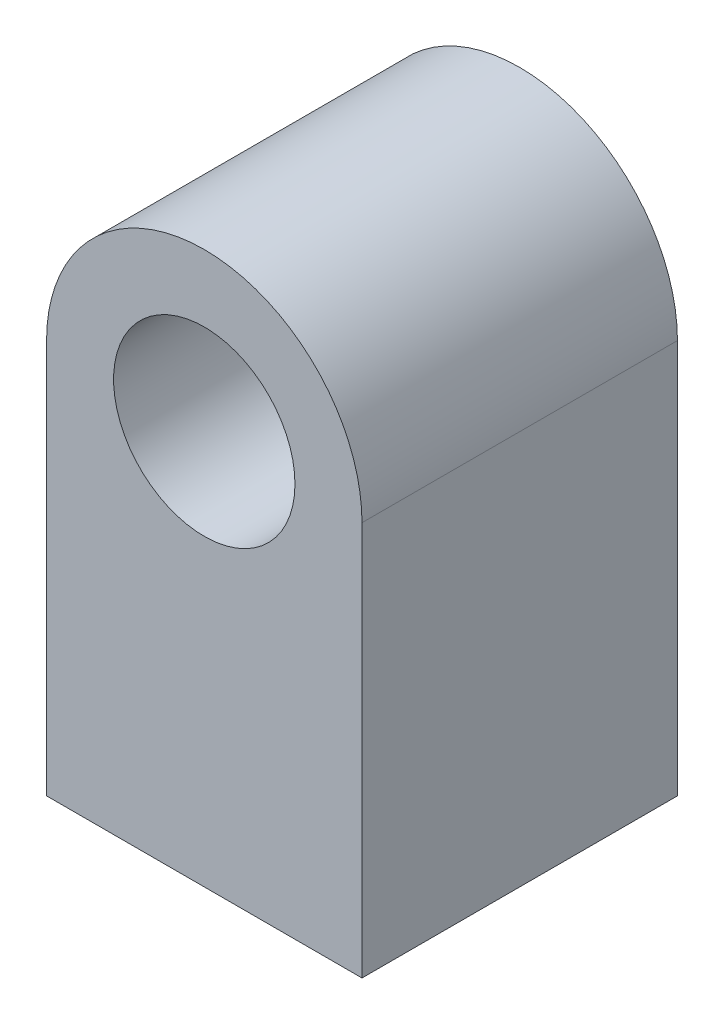
SolidWorks part; units mm, degrees
ref_plane "前视基准面" through (0, 0, 0) normal (0, 0, 1) x (1, 0, 0)
ref_plane "上视基准面" through (0, 0, 0) normal (0, 1, 0) x (1, 0, 0)
ref_plane "右视基准面" through (0, 0, 0) normal (1, 0, 0) x (0, 0, -1)
other "Configuration Table"
sketch "草图1" plane through (0, 0, 0) normal (0, 0, 1) x (1, 0, 0)
  line L0 (2, 0) -> (2, -5)
  line L1 (2, -5) -> (-2, -5)
  line L2 (-2, -5) -> (-2, 0)
  arc A0 (2, 0) -> (-2, 0) centre (0, 0) ccw
  circle A1 centre (0, 0) radius 1.15
  dimension "D1" = 2.3
  dimension "D2" = 2
  dimension "D3" = 5
extrude "凸台-拉伸1" add sketch "草图1" along normal blind 4
sketch "草图2" plane through (0, -5, 0) normal (0, -1, 0) x (1, 0, 0)
  line L0 (-2, 4) -> (-2, 0) construction
  circle A0 centre (0, 2) radius 1
  point P2 (0, 0)
  point P4 (0, 0)
  point P7 (-2, 2)
  dimension "D1" = 2
extrude "切除-拉伸1" cut sketch "草图2" against normal blind 3.5
